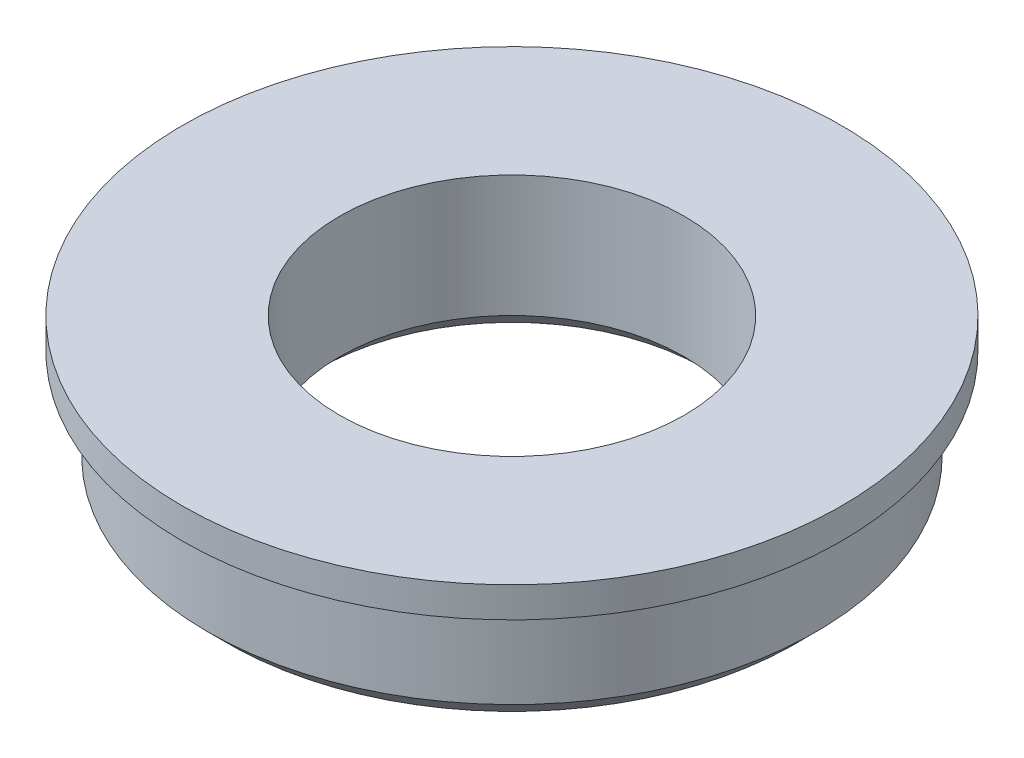
SolidWorks part; units mm, degrees
material "合金钢"
ref_plane "前视基准面" through (0, 0, 0) normal (0, 0, 1) x (1, 0, 0)
ref_plane "上视基准面" through (0, 0, 0) normal (0, 1, 0) x (1, 0, 0)
ref_plane "右视基准面" through (0, 0, 0) normal (1, 0, 0) x (0, 0, -1)
sketch "草图1" plane through (0, 0, 0) normal (0, 0, 1) x (1, 0, 0)
  line L0 (0, 46.2298) -> (0, -33.1091) construction
  line L1 (-49.4491, 0) -> (51.644, 0) construction
  line L2 (-8.5, 0) -> (-15, 0)
  line L3 (-15, 0) -> (-15, 5.5)
  line L4 (-15, 5.5) -> (-16.25, 5.5)
  line L5 (-16.25, 5.5) -> (-16.25, 7)
  line L6 (-16.25, 7) -> (-8.5, 7)
  line L7 (-8.5, 7) -> (-8.5, 0)
  point P7 (-15, 4.2701)
  dimension "D1" = 17
  dimension "D2" = 30
  dimension "D3" = 32.5
  dimension "D4" = 7
  dimension "D5" = 1.5
revolve "旋转1" add sketch "草图1" angle 360 about L0
chamfer "倒角1" distance 1 angle 45 2 edges at (0, 0, 8.5) (0, 0, 15)
